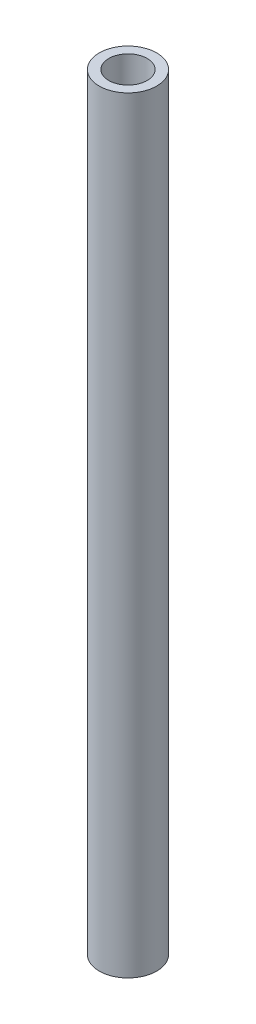
SolidWorks part; units mm, degrees
material "Silicon Rubber"
ref_plane "Front Plane" through (0, 0, 0) normal (0, 0, 1) x (1, 0, 0)
ref_plane "Top Plane" through (0, 0, 0) normal (0, 1, 0) x (1, 0, 0)
ref_plane "Right Plane" through (0, 0, 0) normal (1, 0, 0) x (0, 0, -1)
sketch "Sketch1" plane through (0, 0, 0) normal (0, 1, 0) x (1, 0, 0)
  circle A0 centre (0, 0) radius 4.7625
  circle A1 centre (0, 0) radius 3.175
  dimension "D1" = 9.525
  dimension "D2" = 6.35
extrude "Boss-Extrude1" add sketch "Sketch1" along normal blind 127
